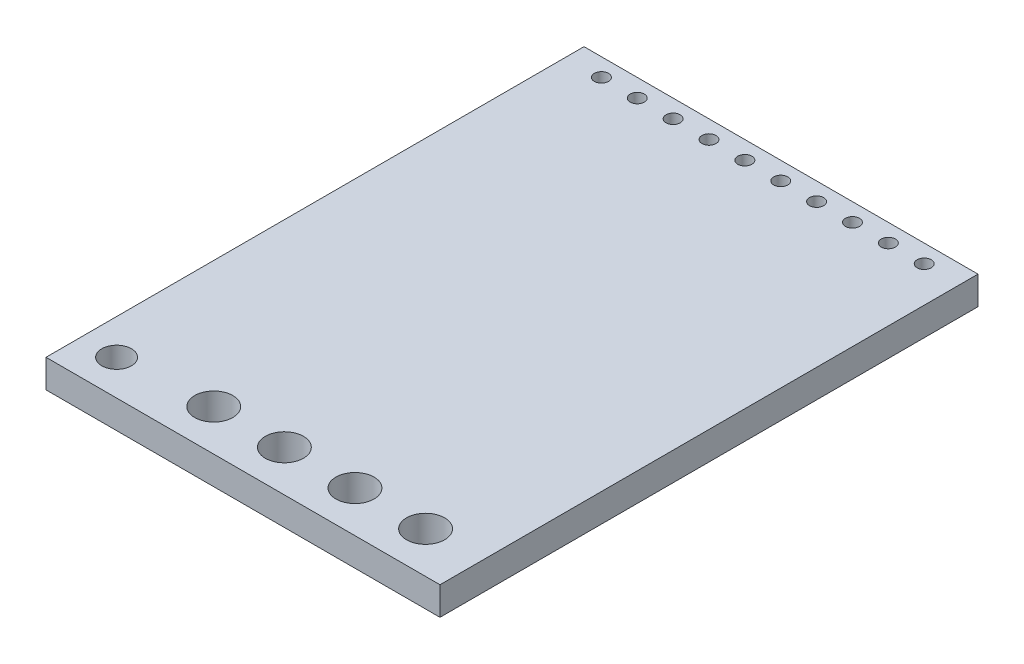
SolidWorks part; units mm, degrees
ref_plane "Front Plane" through (0, 0, 0) normal (0, 0, 1) x (1, 0, 0)
ref_plane "Top Plane" through (0, 0, 0) normal (0, 1, 0) x (1, 0, 0)
ref_plane "Right Plane" through (0, 0, 0) normal (1, 0, 0) x (0, 0, -1)
sketch "Sketch1" plane through (0, 0, 0) normal (0, 1, 0) x (1, 0, 0)
  line L1 (-13.95, -19.05) -> (13.95, -19.05)
  line L2 (-13.95, -19.05) -> (-13.95, 19.05)
  line L3 (-13.95, 19.05) -> (13.95, 19.05)
  line L4 (13.95, -19.05) -> (13.95, 19.05)
  line L5 (-13.95, -19.05) -> (13.95, 19.05) construction
  line L6 (-13.95, 19.05) -> (13.95, -19.05) construction
  circle A1 centre (-11.45, -16.55) radius 1.05
  circle A2 centre (11.41, 17.78) radius 0.5
  circle A3 centre (8.87, 17.78) radius 0.5
  circle A4 centre (6.33, 17.78) radius 0.5
  circle A5 centre (3.79, 17.78) radius 0.5
  circle A6 centre (1.25, 17.78) radius 0.5
  circle A7 centre (-1.29, 17.78) radius 0.5
  circle A8 centre (-3.83, 17.78) radius 0.5
  circle A9 centre (-6.37, 17.78) radius 0.5
  circle A10 centre (-8.91, 17.78) radius 0.5
  circle A11 centre (-11.45, 17.78) radius 0.5
  circle A12 centre (10.01, -16.13) radius 1.35
  circle A13 centre (5.01, -16.13) radius 1.35
  circle A14 centre (0.01, -16.13) radius 1.35
  circle A15 centre (-4.99, -16.13) radius 1.35
  point P0 (0, 0)
  dimension "D3" = 2.5
  dimension "D4" = 2.5
  dimension "D5" = 2.1
  dimension "D8" = 1
  dimension "D10" = 2.5
  dimension "D11" = 2.92
  dimension "D12" = 2.7
  dimension "D1" = 27.9
  dimension "D2" = 38.1
  dimension "D6" = 1.27
  dimension "D7" = 2.54
  dimension "D13" = 3.94
  dimension "D15" = 5
  dimension "D9" = 10
  dimension "D14" = 4
extrude "Boss-Extrude1" add sketch "Sketch1" along normal blind 2
